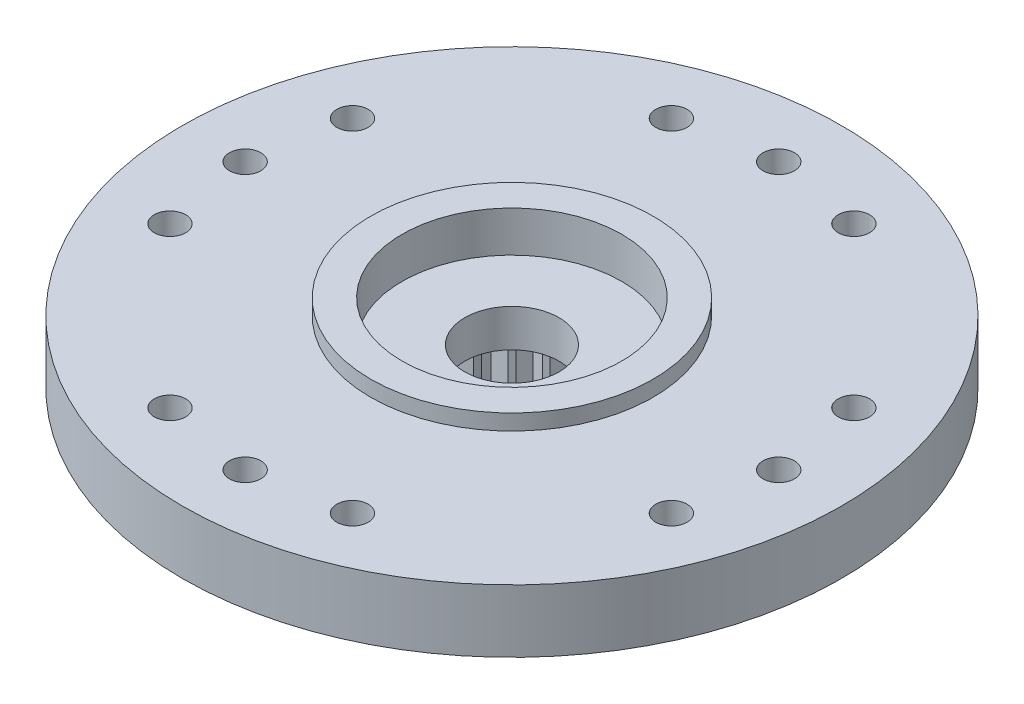
SolidWorks part; units mm, degrees
ref_plane "Front Plane" through (0, 0, 0) normal (0, 0, 1) x (1, 0, 0)
ref_plane "Top Plane" through (0, 0, 0) normal (0, 1, 0) x (1, 0, 0)
ref_plane "Right Plane" through (0, 0, 0) normal (1, 0, 0) x (0, 0, -1)
sketch "Sketch1" plane through (0, 0, 0) normal (0, 1, 0) x (1, 0, 0)
  line L0 (0, 10.5) -> (0, -10.5) construction
  line L1 (-10.5, 0) -> (10.5, 0) construction
  line L2 (0, 0) -> (3.4202, 9.3969) construction
  line L3 (-3.4202, 9.3969) -> (0, 0) construction
  line L4 (0, 0) -> (7.9874, 2.9072) construction
  line L5 (0, 0) -> (7.9874, -2.9072) construction
  circle A0 centre (0, 0) radius 10.5
  circle A1 centre (0, 0) radius 1.5
  circle A2 centre (0, 0) radius 7 construction
  circle A3 centre (0, 0) radius 10 construction
  circle A4 centre (0, 0) radius 8.5 construction
  circle A5 centre (2.9072, 7.9874) radius 0.5
  circle A6 centre (-2.9072, 7.9874) radius 0.5
  circle A7 centre (2.9072, -7.9874) radius 0.5
  circle A8 centre (-2.9072, -7.9874) radius 0.5
  circle A9 centre (0, -8.5) radius 0.5
  circle A11 centre (8.5, 0) radius 0.5
  circle A12 centre (7.9874, 2.9072) radius 0.5
  circle A13 centre (7.9874, -2.9072) radius 0.5
  circle A20 centre (-7.9874, -2.9072) radius 0.5
  circle A21 centre (-8.5, 0) radius 0.5
  circle A22 centre (-7.9874, 2.9072) radius 0.5
  circle A23 centre (0, 8.5) radius 0.5
  dimension "D1" = 21
  dimension "D2" = 3
  dimension "D3" = 14
  dimension "D4" = 20
  dimension "D5" = 17
  dimension "D6" = 1
  dimension "D7" = 1
  dimension "D16" = 1
  dimension "D17" = 1
  dimension "D18" = 1
  dimension "D19" = 1
  dimension "D8" = 20
  dimension "D10" = 20
  dimension "D14" = 20
  dimension "D15" = 20
extrude "Boss-Extrude1" add sketch "Sketch1" along normal blind 2
sketch "Sketch2" plane through (0, 2, 0) normal (0, 1, 0) x (1, 0, 0)
  circle A0 centre (0, 0) radius 4.5
  circle A1 centre (0, 0) radius 3.5
  dimension "D1" = 9
  dimension "D2" = 1
extrude "Boss-Extrude2" add sketch "Sketch2" along normal blind 0.5
sketch "Sketch3" plane through (0, 2, 0) normal (0, 1, 0) x (1, 0, 0)
  circle A0 centre (0, 0) radius 1.5 construction
  circle A1 centre (0, 0) radius 3.5 construction
  circle A2 centre (0, 0) radius 1.5
  circle A3 centre (0, 0) radius 3.5
extrude "Cut-Extrude1" cut sketch "Sketch3" against normal blind 0.8
sketch "Sketch4" plane through (0, 0, 0) normal (0, -1, 0) x (1, 0, 0)
  circle A0 centre (0, 0) radius 4.5
  circle A1 centre (0, 0) radius 2.5
  dimension "D1" = 9
  dimension "D2" = 2
extrude "Boss-Extrude3" add sketch "Sketch4" along normal blind 2.5
sketch "Sketch5" plane through (0, -2.5, 0) normal (0, -1, 0) x (1, 0, 0)
  line L0 (0, 0) -> (0, 0.6245) construction
  line L1 (0, 3) -> (-0.299, 2.4821)
  line L2 (0, 3) -> (0.299, 2.4821)
  line L3 (0.9271, 2.8532) -> (0.4826, 2.453)
  line L4 (0.9271, 2.8532) -> (1.0514, 2.2682)
  line L5 (1.7634, 2.4271) -> (1.217, 2.1838)
  line L6 (1.7634, 2.4271) -> (1.7008, 1.8323)
  line L7 (2.4271, 1.7634) -> (1.8323, 1.7008)
  line L8 (2.4271, 1.7634) -> (2.1838, 1.217)
  line L9 (2.8532, 0.9271) -> (2.2682, 1.0514)
  line L10 (2.8532, 0.9271) -> (2.453, 0.4826)
  line L11 (3, 0) -> (2.4821, 0.299)
  line L12 (3, 0) -> (2.4821, -0.299)
  line L13 (2.8532, -0.9271) -> (2.453, -0.4826)
  line L14 (2.8532, -0.9271) -> (2.2682, -1.0514)
  line L15 (2.4271, -1.7634) -> (2.1838, -1.217)
  line L16 (2.4271, -1.7634) -> (1.8323, -1.7008)
  line L17 (1.7634, -2.4271) -> (1.7008, -1.8323)
  line L18 (1.7634, -2.4271) -> (1.217, -2.1838)
  line L19 (0.9271, -2.8532) -> (1.0514, -2.2682)
  line L20 (0.9271, -2.8532) -> (0.4826, -2.453)
  line L21 (0, -3) -> (0.299, -2.4821)
  line L22 (0, -3) -> (-0.299, -2.4821)
  line L23 (-0.9271, -2.8532) -> (-0.4826, -2.453)
  line L24 (-0.9271, -2.8532) -> (-1.0514, -2.2682)
  line L25 (-1.7634, -2.4271) -> (-1.217, -2.1838)
  line L26 (-1.7634, -2.4271) -> (-1.7008, -1.8323)
  line L27 (-2.4271, -1.7634) -> (-1.8323, -1.7008)
  line L28 (-2.4271, -1.7634) -> (-2.1838, -1.217)
  line L29 (-2.8532, -0.9271) -> (-2.2682, -1.0514)
  line L30 (-2.8532, -0.9271) -> (-2.453, -0.4826)
  line L31 (-3, 0) -> (-2.4821, -0.299)
  line L32 (-3, 0) -> (-2.4821, 0.299)
  line L33 (-2.8532, 0.9271) -> (-2.453, 0.4826)
  line L34 (-2.8532, 0.9271) -> (-2.2682, 1.0514)
  line L35 (-2.4271, 1.7634) -> (-2.1838, 1.217)
  line L36 (-2.4271, 1.7634) -> (-1.8323, 1.7008)
  line L37 (-1.7634, 2.4271) -> (-1.7008, 1.8323)
  line L38 (-1.7634, 2.4271) -> (-1.217, 2.1838)
  line L39 (-0.9271, 2.8532) -> (-1.0514, 2.2682)
  line L40 (-0.9271, 2.8532) -> (-0.4826, 2.453)
  circle A0 centre (0, 0) radius 2.5 construction
  arc A1 (-2.1838, 1.217) -> (-2.2682, 1.0514) centre (0, 0) ccw
  arc A2 (-1.7008, 1.8323) -> (-1.8323, 1.7008) centre (0, 0) ccw
  arc A3 (-1.0514, 2.2682) -> (-1.217, 2.1838) centre (0, 0) ccw
  arc A4 (-0.299, 2.4821) -> (-0.4826, 2.453) centre (0, 0) ccw
  arc A5 (0.4826, 2.453) -> (0.299, 2.4821) centre (0, 0) ccw
  arc A6 (1.217, 2.1838) -> (1.0514, 2.2682) centre (0, 0) ccw
  arc A7 (1.8323, 1.7008) -> (1.7008, 1.8323) centre (0, 0) ccw
  arc A8 (2.2682, 1.0514) -> (2.1838, 1.217) centre (0, 0) ccw
  arc A9 (2.4821, 0.299) -> (2.453, 0.4826) centre (0, 0) ccw
  arc A10 (2.453, -0.4826) -> (2.4821, -0.299) centre (0, 0) ccw
  arc A11 (2.1838, -1.217) -> (2.2682, -1.0514) centre (0, 0) ccw
  arc A12 (1.7008, -1.8323) -> (1.8323, -1.7008) centre (0, 0) ccw
  arc A13 (1.0514, -2.2682) -> (1.217, -2.1838) centre (0, 0) ccw
  arc A14 (0.299, -2.4821) -> (0.4826, -2.453) centre (0, 0) ccw
  arc A15 (-0.4826, -2.453) -> (0, -2.5) centre (0, 0) ccw
  arc A16 (-1.217, -2.1838) -> (-1.0514, -2.2682) centre (0, 0) ccw
  arc A17 (-1.8323, -1.7008) -> (-1.7008, -1.8323) centre (0, 0) ccw
  arc A18 (-2.2682, -1.0514) -> (-2.1838, -1.217) centre (0, 0) ccw
  arc A19 (-2.4821, -0.299) -> (-2.453, -0.4826) centre (0, 0) ccw
  arc A20 (-2.453, 0.4826) -> (-2.4821, 0.299) centre (0, 0) ccw
  point P68 (0, 0)
  circle M5 centre (0, 0) radius 2.5
  dimension "D1" = 30
  dimension "D2" = 3
  dimension "D3" = 20
extrude "Cut-Extrude3" cut sketch "Sketch5" against normal up to surface (2.5 mm away) contours L36 L35 M5 | L34 L33 M5 | L32 L31 M5 | L30 L29 M5 | L28 L27 M5 | L26 L25 M5 | L24 L23 M5 | L0 L21 M5 | L22 L0 M5 | L20 L19 M5 | L18 L17 M5 | L16 L15 M5 | L14 L13 M5 | L12 L11 M5 | L10 L9 M5 | L8 L7 M5 | L6 L5 M5 | L4 L3 M5 | L0 L2 M5 | L0 L1 M5 | L40 L39 M5 | L38 L37 M5
